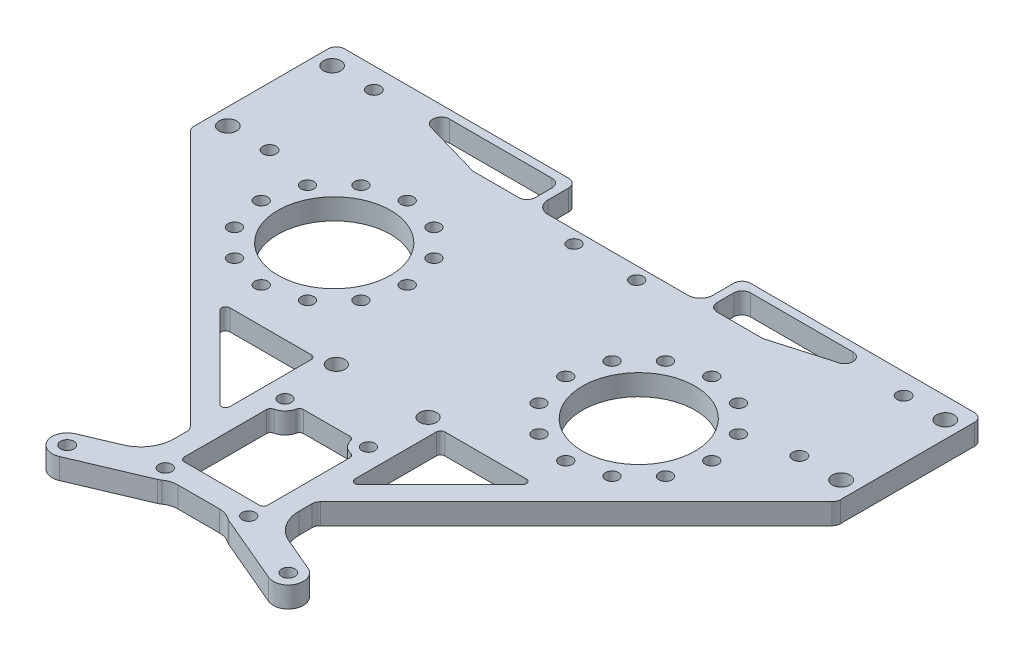
SolidWorks part; units mm, degrees
material "Thornel Mat VMA"
ref_plane "前视基准面" through (0, 0, 0) normal (0, 0, 1) x (1, 0, 0)
ref_plane "上视基准面" through (0, 0, 0) normal (0, 1, 0) x (1, 0, 0)
ref_plane "右视基准面" through (0, 0, 0) normal (1, 0, 0) x (0, 0, -1)
other "Configuration Table"
sketch "草图1" plane through (0, 0, 0) normal (0, 1, 0) x (1, 0, 0)
  line L0 (0, -60.6435) -> (0, 66.087) construction
  line L1 (-77.5, 31.5) -> (77.5, 31.5)
  line L2 (-77.5, 31.5) -> (-77.5, -29)
  line L3 (-77.5, -29) -> (77.5, -29)
  line L4 (77.5, 31.5) -> (77.5, -29)
  circle A0 centre (36.5, 0) radius 13.5
  circle A1 centre (-36.5, 0) radius 13.5
  circle A2 centre (36.5, 17.5) radius 1.55
  circle A3 centre (45.25, 15.1554) radius 1.55
  circle A4 centre (51.6554, 8.75) radius 1.55
  circle A5 centre (54, 0) radius 1.55
  circle A6 centre (51.6554, -8.75) radius 1.55
  circle A7 centre (45.25, -15.1554) radius 1.55
  circle A8 centre (36.5, -17.5) radius 1.55
  circle A9 centre (27.75, -15.1554) radius 1.55
  circle A10 centre (21.3446, -8.75) radius 1.55
  circle A11 centre (19, 0) radius 1.55
  circle A12 centre (21.3446, 8.75) radius 1.55
  circle A13 centre (27.75, 15.1554) radius 1.55
  circle A14 centre (-36.5, 17.5) radius 1.55
  circle A15 centre (-27.75, 15.1554) radius 1.55
  circle A16 centre (-21.3446, 8.75) radius 1.55
  circle A17 centre (-19, 0) radius 1.55
  circle A18 centre (-21.3446, -8.75) radius 1.55
  circle A19 centre (-27.75, -15.1554) radius 1.55
  circle A20 centre (-36.5, -17.5) radius 1.55
  circle A21 centre (-45.25, -15.1554) radius 1.55
  circle A22 centre (-51.6554, -8.75) radius 1.55
  circle A23 centre (-54, 0) radius 1.55
  circle A24 centre (-51.6554, 8.75) radius 1.55
  circle A25 centre (-45.25, 15.1554) radius 1.55
  point P0 (0, 0)
  point P38 (36.5, 0)
  point P40 (0, -29)
  point P63 (-36.5, 0)
  dimension "D3" = 27
  dimension "D7" = 3.1
  dimension "D1" = 155
  dimension "D2" = 29
  dimension "D4" = 73
  dimension "D6" = 17.5
  dimension "D10" = 31.5
  dimension "D8" = 12
  dimension "D9" = 12
extrude "凸台-拉伸1" add sketch "草图1" along normal blind 5
sketch "草图3" plane through (0, 5, 0) normal (0, 1, 0) x (1, 0, 0)
  line L0 (-77.5, -29) -> (77.5, -29) construction
  line L1 (-15, -29) -> (15, -29)
  line L2 (-15, -29) -> (-15, -69)
  line L3 (-15, -69) -> (15, -69)
  line L4 (15, -29) -> (15, -69)
  point P6 (0, -29)
  dimension "D1" = 30
  dimension "D2" = 40
extrude "凸台-拉伸2" add sketch "草图3" against normal up to surface (5 mm away) up to face at (0, 0, -1.25)
sketch "草图4" plane through (0, 5, 0) normal (0, 1, 0) x (1, 0, 0)
  line L0 (77.5, -29) -> (77.5, 31.5) construction
  line L1 (-77.5, 31.5) -> (77.5, 31.5)
  line L2 (-77.5, 31.5) -> (-77.5, 41.5)
  line L3 (-77.5, 41.5) -> (77.5, 41.5)
  line L4 (77.5, 31.5) -> (77.5, 41.5)
  dimension "D1" = 10
extrude "凸台-拉伸3" add sketch "草图4" against normal up to surface (5 mm away) up to face at (0, 0, 23.875)
sketch "草图5" plane through (0, 0, 0) normal (0, -1, 0) x (1, 0, 0)
  line L0 (-77.5, -6.5) -> (-42, 29)
  line L1 (-77.5, -41.5) -> (-69.5, -41.5)
  line L2 (-77.5, -41.5) -> (-77.5, -6.5)
  line L3 (-77.5, -6.5) -> (-69.5, -6.5)
  line L4 (-69.5, -41.5) -> (-69.5, -6.5)
  line L5 (-77.5, 29) -> (-15, 29) construction
  line L6 (-42, 29) -> (-77.5, 29)
  line L7 (-77.5, 29) -> (-77.5, -6.5)
  line L8 (-77.5, -41.5) -> (77.5, -41.5) construction
  line L9 (0, -41.5) -> (-69.5, -41.5)
  line L10 (0, -41.5) -> (0, -31.5)
  line L11 (0, -31.5) -> (-69.5, -31.5)
  line L12 (-69.5, -41.5) -> (-69.5, -31.5)
  line L13 (-69.5, -41.5) -> (-34.75, -31.5)
  line M15 (-15, 29) -> (-77.5, 29)
  line M16 (-77.5, 29) -> (-77.5, -41.5)
  line M17 (-77.5, -41.5) -> (77.5, -41.5)
  dimension "D1" = 8
  dimension "D2" = 35
  dimension "D4" = 10
extrude "切除-拉伸1" cut sketch "草图5" against normal through all contours L0 M16 M15 | L13 L10 L11 M17
mirror "镜向1" about plane through (0, 0, 0) normal (1, 0, 0) of "切除-拉伸1"
sketch "草图6" plane through (0, 5, 0) normal (0, 1, 0) x (1, 0, 0)
  line L0 (-77.5, 41.5) -> (-77.5, 6.5) construction
  line L1 (-69.5, 41.5) -> (-77.5, 41.5) construction
  line L2 (0, 0) -> (0, 31.5) construction
  line L3 (34.75, 31.5) -> (-34.75, 31.5) construction
  circle A0 centre (-73.5, 36.5) radius 2.1
  circle A1 centre (-73.5, 11.5) radius 2.1
  circle A2 centre (73.5, 11.5) radius 2.1
  circle A3 centre (73.5, 36.5) radius 2.1
  dimension "D2" = 4.2
  dimension "D1" = 4
  dimension "D3" = 25
  dimension "D4" = 5
extrude "切除-拉伸2" cut sketch "草图6" against normal through all
sketch "草图7" plane through (0, 5, 0) normal (0, 1, 0) x (1, 0, 0)
  circle A0 centre (7.5, 28.5) radius 1.55
  circle A1 centre (-7.5, 28.5) radius 1.55
  circle A2 centre (11, -25) radius 2.05
  circle A3 centre (-11, -25) radius 2.05
  dimension "D1" = 3.1
  dimension "D2" = 4.1
extrude "切除-拉伸3" cut sketch "草图7" against normal through all
sketch "草图10" plane through (0, 5, 0) normal (0, 1, 0) x (1, 0, 0)
  line L0 (-42, -29) -> (-15, -56)
  line L1 (-15, -29) -> (-15, -69) construction
  line L2 (-15, -56) -> (-15, -29)
  line L3 (-15, -29) -> (-42, -29)
  line L4 (15, -29) -> (15, -56)
  line L5 (15, -69) -> (15, -29) construction
  line L6 (15, -56) -> (42, -29)
  line L7 (42, -29) -> (15, -29)
extrude "凸台-拉伸6" add sketch "草图10" against normal blind 5
sketch "草图11" plane through (0, 5, 0) normal (0, 1, 0) x (1, 0, 0)
  line L0 (-73.9645, 10.0355) -> (-11.4645, -52.4645)
  line L1 (11.4645, -52.4645) -> (73.9645, 10.0355)
  line L2 (-15, -56) -> (-15, -26)
  line L3 (-15, -26) -> (-37.9289, -26)
  line L4 (0, -69) -> (0, 0)
  line L5 (15, -56) -> (15, -26)
  line L6 (15, -26) -> (37.9289, -26)
  line L12 (15, -69) -> (15, -56)
  line L13 (15, -56) -> (77.5, 6.5)
  line L14 (77.5, 6.5) -> (77.5, 41.5)
  line L15 (77.5, 41.5) -> (69.5, 41.5)
  line L16 (69.5, 41.5) -> (34.75, 31.5)
  line L17 (34.75, 31.5) -> (-34.75, 31.5)
  line L18 (-34.75, 31.5) -> (-69.5, 41.5)
  line L19 (-69.5, 41.5) -> (-77.5, 41.5)
  line L20 (-77.5, 41.5) -> (-77.5, 6.5)
  line L21 (-77.5, 6.5) -> (-15, -56)
  line L22 (-15, -56) -> (-15, -69)
  line L23 (-15, -69) -> (15, -69)
  line L24 (15, -69) -> (15, -56)
  line L25 (15, -56) -> (77.5, 6.5)
  line L26 (77.5, 6.5) -> (77.5, 41.5)
  line L27 (77.5, 41.5) -> (69.5, 41.5)
  line L28 (69.5, 41.5) -> (34.75, 31.5)
  line L29 (34.75, 31.5) -> (-34.75, 31.5)
  line L30 (-34.75, 31.5) -> (-69.5, 41.5)
  line L31 (-69.5, 41.5) -> (-77.5, 41.5)
  line L32 (-77.5, 41.5) -> (-77.5, 6.5)
  line L33 (-77.5, 6.5) -> (-15, -56)
  line L34 (-15, -56) -> (-15, -69)
  line L35 (-15, -69) -> (15, -69)
  dimension "D3" = 30
  dimension "D1" = 0
  dimension "D2" = 5
extrude "切除-拉伸4" cut sketch "草图11" against normal blind 5 contours L2 L3 L0 | L6 L5 L1
sketch "草图13" plane through (0, 5, 0) normal (0, 1, 0) x (1, 0, 0)
  line L0 (10, -63.45) -> (-10, -63.45)
  line L1 (-10, -38.3) -> (10, -38.3)
  line L2 (-10, -38.3) -> (-10, -67)
  line L3 (-10, -67) -> (10, -67)
  line L4 (10, -38.3) -> (10, -67)
  line L5 (-10, -38.3) -> (10, -67) construction
  line L6 (-10, -67) -> (10, -38.3) construction
  line L7 (15, -69) -> (15, -56) construction
  line L8 (-15, -69) -> (15, -69) construction
  circle A0 centre (-10, -38.3) radius 1.55
  circle A1 centre (10, -38.3) radius 1.55
  circle A2 centre (-10, -67) radius 1.55
  circle A3 centre (10, -67) radius 1.55
  circle A4 centre (-10, -38.3) radius 3.55
  circle A5 centre (10, -38.3) radius 3.55
  circle A6 centre (10, -67) radius 3.55
  circle A7 centre (-10, -67) radius 3.55
  point P0 (0, -52.65)
  dimension "D5" = 3.1
  dimension "D1" = 20
  dimension "D2" = 28.7
  dimension "D3" = 5
  dimension "D4" = 2
  dimension "D6" = 2
extrude "切除-拉伸5" cut sketch "草图13" against normal through all contours L1 A0 L2 | L2 A0 L1 | A7 L3 A6 L4 A5 L1 A4 L2 | L4 A1 L1 | L1 A1 L4 | L3 A3 L4 | L4 A3 L3 | L2 A2 L3 | L3 A2 L2
fillet "圆角1" radius 1 12 edges at (-10, 2.5, 41.85) (-6.45, 2.5, 38.3) (6.45, 2.5, 38.3) (10, 2.5, 41.85) (-37.9289, 2.5, 26) (-15, 2.5, 26) (-15, 2.5, 48.9289) (15, 2.5, 48.9289) (15, 2.5, 26) (37.9289, 2.5, 26) (10, 2.5, 63.45) (-10, 2.5, 63.45)
fillet "圆角2" radius 2 12 edges at (77.5, 2.5, -6.5) (77.5, 2.5, -41.5) (69.5, 2.5, -41.5) (34.75, 2.5, -31.5) (-34.75, 2.5, -31.5) (-69.5, 2.5, -41.5) (-77.5, 2.5, -41.5) (-77.5, 2.5, -6.5) (-15, 2.5, 56) (-15, 2.5, 69) (15, 2.5, 56) (15, 2.5, 69)
sketch "草图14" plane through (0, 5, 0) normal (0, 1, 0) x (1, 0, 0)
  line L0 (-69.782, 41.5) -> (-19.782, 41.5)
  line L1 (-19.782, 41.5) -> (-19.782, 31.5)
  line L2 (0, 0) -> (0, 31.5) construction
  line L3 (-69.782, 39.5) -> (-21.782, 39.5)
  line L4 (-21.782, 39.5) -> (-21.782, 31.5)
  line L12 (15.5858, -55.4142) -> (76.9142, 5.9142)
  line L13 (77.5, 7.3284) -> (77.5, 39.5)
  line L14 (75.5, 41.5) -> (69.782, 41.5)
  line L15 (69.229, 41.422) -> (35.021, 31.578)
  line L16 (34.468, 31.5) -> (-34.468, 31.5)
  line L17 (-35.021, 31.578) -> (-69.229, 41.422)
  line L18 (-69.782, 41.5) -> (-75.5, 41.5)
  line L19 (-77.5, 39.5) -> (-77.5, 7.3284)
  line L20 (-76.9142, 5.9142) -> (-15.5858, -55.4142)
  line L21 (-15, -56.8284) -> (-15, -67)
  line L22 (-13, -69) -> (13, -69)
  line L23 (15, -67) -> (15, -56.8284)
  line L24 (15.5858, -55.4142) -> (76.9142, 5.9142)
  line L25 (77.5, 7.3284) -> (77.5, 39.5)
  line L26 (75.5, 41.5) -> (69.782, 41.5)
  line L27 (69.229, 41.422) -> (35.021, 31.578)
  line L28 (34.468, 31.5) -> (-34.468, 31.5)
  line L29 (-35.021, 31.578) -> (-69.229, 41.422)
  line L30 (-69.782, 41.5) -> (-75.5, 41.5)
  line L31 (-77.5, 39.5) -> (-77.5, 7.3284)
  line L32 (-76.9142, 5.9142) -> (-15.5858, -55.4142)
  line L33 (-15, -56.8284) -> (-15, -67)
  line L34 (-13, -69) -> (13, -69)
  line L35 (15, -67) -> (15, -56.8284)
  arc A12 (76.9142, 5.9142) -> (77.5, 7.3284) centre (75.5, 7.3284) ccw
  arc A13 (77.5, 39.5) -> (75.5, 41.5) centre (75.5, 39.5) ccw
  arc A14 (69.782, 41.5) -> (69.229, 41.422) centre (69.782, 39.5) ccw
  arc A15 (34.468, 31.5) -> (35.021, 31.578) centre (34.468, 33.5) ccw
  arc A16 (-35.021, 31.578) -> (-34.468, 31.5) centre (-34.468, 33.5) ccw
  arc A17 (-69.229, 41.422) -> (-69.782, 41.5) centre (-69.782, 39.5) ccw
  arc A18 (-75.5, 41.5) -> (-77.5, 39.5) centre (-75.5, 39.5) ccw
  arc A19 (-77.5, 7.3284) -> (-76.9142, 5.9142) centre (-75.5, 7.3284) ccw
  arc A20 (-15, -56.8284) -> (-15.5858, -55.4142) centre (-17, -56.8284) ccw
  arc A21 (-15, -67) -> (-13, -69) centre (-13, -67) ccw
  arc A22 (13, -69) -> (15, -67) centre (13, -67) ccw
  arc A23 (15.5858, -55.4142) -> (15, -56.8284) centre (17, -56.8284) ccw
  arc A24 (76.9142, 5.9142) -> (77.5, 7.3284) centre (75.5, 7.3284) ccw
  arc A25 (77.5, 39.5) -> (75.5, 41.5) centre (75.5, 39.5) ccw
  arc A26 (69.782, 41.5) -> (69.229, 41.422) centre (69.782, 39.5) ccw
  arc A27 (34.468, 31.5) -> (35.021, 31.578) centre (34.468, 33.5) ccw
  arc A28 (-35.021, 31.578) -> (-34.468, 31.5) centre (-34.468, 33.5) ccw
  arc A29 (-69.229, 41.422) -> (-69.782, 41.5) centre (-69.782, 39.5) ccw
  arc A30 (-75.5, 41.5) -> (-77.5, 39.5) centre (-75.5, 39.5) ccw
  arc A31 (-77.5, 7.3284) -> (-76.9142, 5.9142) centre (-75.5, 7.3284) ccw
  arc A32 (-15, -56.8284) -> (-15.5858, -55.4142) centre (-17, -56.8284) ccw
  arc A33 (-15, -67) -> (-13, -69) centre (-13, -67) ccw
  arc A34 (13, -69) -> (15, -67) centre (13, -67) ccw
  arc A35 (15.5858, -55.4142) -> (15, -56.8284) centre (17, -56.8284) ccw
  dimension "D2" = 50
  dimension "D1" = 0
  dimension "D3" = 2
extrude "凸台-拉伸8" add sketch "草图14" against normal blind 5 contours A29 L29 L3 L4 L28 L1 L0
mirror "镜向2" about plane through (0, 0, 0) normal (1, 0, 0) of "凸台-拉伸8"
fillet "圆角3" radius 2 8 edges at (-19.782, 2.5, -41.5) (-21.782, 2.5, -31.5) (-21.782, 2.5, -39.5) (-62.55, 2.5, -39.5) (62.55, 2.5, -39.5) (21.782, 2.5, -39.5) (21.782, 2.5, -31.5) (19.782, 2.5, -41.5)
fillet "圆角4" radius 3 2 edges at (-19.782, 2.5, -31.5) (19.782, 2.5, -31.5)
sketch "草图15" plane through (0, 5, 0) normal (0, 1, 0) x (1, 0, 0)
  line L0 (26.5, -74) -> (10, -67) construction
  line L1 (25.094, -77.3141) -> (8.594, -70.3141)
  line L2 (27.906, -70.6859) -> (11.406, -63.6859)
  line L3 (-26.5, -74) -> (-10, -67) construction
  line L4 (-27.906, -70.6859) -> (-11.406, -63.6859)
  line L5 (-25.094, -77.3141) -> (-8.594, -70.3141)
  circle A2 centre (-26.5, -74) radius 1.6
  circle A3 centre (26.5, -74) radius 1.6
  circle A4 centre (26.5, -74) radius 3.6
  circle A5 centre (-26.5, -74) radius 3.6
  arc A6 (25.094, -77.3141) -> (27.906, -70.6859) centre (26.5, -74) ccw
  arc A7 (11.406, -63.6859) -> (8.594, -70.3141) centre (10, -67) ccw
  arc A8 (-27.906, -70.6859) -> (-25.094, -77.3141) centre (-26.5, -74) ccw
  arc A9 (-8.594, -70.3141) -> (-11.406, -63.6859) centre (-10, -67) ccw
  circle A10 centre (10, -67) radius 1.55 construction
  circle A11 centre (-10, -67) radius 1.55 construction
  circle A12 centre (10, -67) radius 1.55
  circle A13 centre (-10, -67) radius 1.55
  point P8 (18.25, -70.5)
  point P14 (-18.25, -70.5)
  dimension "D1" = 2
extrude "凸台-拉伸9" add sketch "草图15" against normal blind 5 contours L2 A7 L1 A4 | A4 A3 | L5 A9 L4 A5 | A5 A2
fillet "圆角5" radius 5 2 edges at (7.0067, 2.5, 69) (-7.0067, 2.5, 69)
fillet "圆角6" radius 8 2 edges at (15, 2.5, 65.2106) (-15, 2.5, 65.2106)
sketch "草图16" plane through (0, 5, 0) normal (0, 1, 0) x (1, 0, 0)
  line L0 (77.5, 7.3284) -> (77.5, 39.5) construction
  line L1 (-63.5, 36.5) -> (63.5, 36.5) construction
  line L2 (-63.5, 36.5) -> (-63.5, 11.5) construction
  line L3 (-63.5, 11.5) -> (63.5, 11.5) construction
  line L4 (63.5, 36.5) -> (63.5, 11.5) construction
  line L5 (-77.5, 39.5) -> (-77.5, 7.3284) construction
  line L6 (-63.5, 36.5) -> (-73.5, 36.5) construction
  circle A0 centre (-63.5, 36.5) radius 1.6
  circle A1 centre (-63.5, 11.5) radius 1.6
  circle A2 centre (63.5, 11.5) radius 1.6
  circle A3 centre (63.5, 36.5) radius 1.6
  dimension "D4" = 3.2
  dimension "D1" = 14
  dimension "D2" = 14
  dimension "D3" = 25
extrude "切除-拉伸6" cut sketch "草图16" against normal through all
